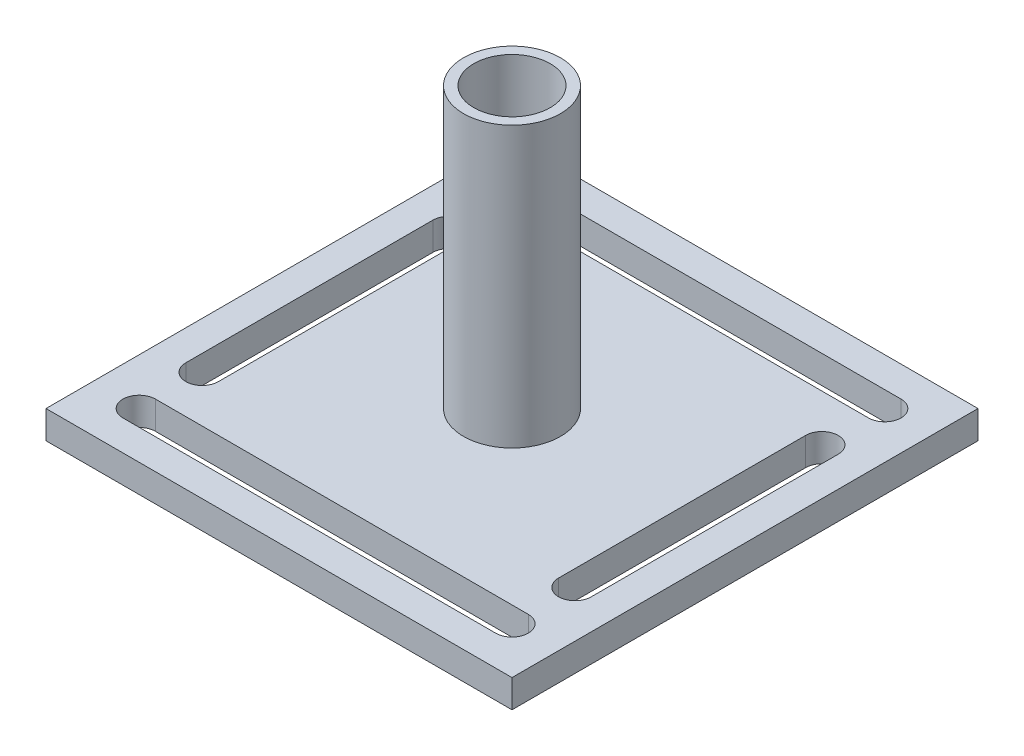
SolidWorks part; units mm, degrees
ref_plane "前视基准面" through (0, 0, 0) normal (0, 0, 1) x (1, 0, 0)
ref_plane "上视基准面" through (0, 0, 0) normal (0, 1, 0) x (1, 0, 0)
ref_plane "右视基准面" through (0, 0, 0) normal (1, 0, 0) x (0, 0, -1)
other "Configuration Table"
sketch "草图1" plane through (0, 0, 0) normal (0, 1, 0) x (1, 0, 0)
  line L1 (0, 0) -> (50, 0)
  line L2 (0, 0) -> (0, 50)
  line L3 (0, 50) -> (50, 50)
  line L4 (50, 0) -> (50, 50)
  dimension "D1" = 50
  dimension "D2" = 50
extrude "凸台-拉伸1" add sketch "草图1" along normal blind 3
sketch "草图2" plane through (0, 3, 0) normal (0, 1, 0) x (1, 0, 0)
  line L0 (0, 25) -> (50, 25) construction
  line L1 (0, 50) -> (0, 0) construction
  line L2 (50, 0) -> (50, 50) construction
  circle A0 centre (25, 25) radius 5.2
extrude "凸台-拉伸3" add sketch "草图2" along normal blind 30
sketch "草图4" plane through (0, 33, 0) normal (0, 1, 0) x (1, 0, 0)
  line L0 (19.8, 25) -> (30.2, 25) construction
  circle A0 centre (25, 25) radius 5.2 construction
  circle A1 centre (25, 25) radius 5.2 construction
  circle A2 centre (25, 25) radius 4.1
extrude "切除-拉伸1" cut sketch "草图4" against normal blind 30
sketch "草图6" plane through (0, 0, 0) normal (0, -1, 0) x (1, 0, 0)
  line L0 (50, -5) -> (45, -5) construction
  line L3 (0, -5) -> (5, -5) construction
  line L4 (5, 0) -> (5, -5) construction
  line L5 (50, 0) -> (50, -50) construction
  line L6 (5, -5) -> (45, -5) construction
  line L7 (5, -3.25) -> (45, -3.25)
  line L8 (5, -6.75) -> (45, -6.75)
  line L9 (5, -6.75) -> (5, -11.75)
  line L10 (0, -25) -> (50, -25) construction
  line L11 (0, -50) -> (0, 0) construction
  line L12 (5, -45) -> (45, -45) construction
  line L13 (5, -46.75) -> (45, -46.75)
  line L14 (5, -43.25) -> (45, -43.25)
  line L15 (5, -43.25) -> (5, -38.25)
  line L16 (5, -11.75) -> (5, -38.25) construction
  line L17 (6.75, -11.75) -> (6.75, -38.25)
  line L18 (3.25, -11.75) -> (3.25, -38.25)
  line L19 (25, 0) -> (25, -50) construction
  line L20 (0, 0) -> (50, 0) construction
  line L21 (50, -50) -> (0, -50) construction
  line L22 (45, -11.75) -> (45, -38.25) construction
  line L23 (43.25, -11.75) -> (43.25, -38.25)
  line L24 (46.75, -11.75) -> (46.75, -38.25)
  arc A0 (5, -3.25) -> (5, -6.75) centre (5, -5) ccw
  arc A1 (45, -6.75) -> (45, -3.25) centre (45, -5) ccw
  arc A2 (5, -46.75) -> (5, -43.25) centre (5, -45) cw
  arc A3 (45, -43.25) -> (45, -46.75) centre (45, -45) cw
  arc A4 (6.75, -11.75) -> (3.25, -11.75) centre (5, -11.75) ccw
  arc A5 (3.25, -38.25) -> (6.75, -38.25) centre (5, -38.25) ccw
  arc A6 (43.25, -11.75) -> (46.75, -11.75) centre (45, -11.75) cw
  arc A7 (46.75, -38.25) -> (43.25, -38.25) centre (45, -38.25) cw
  point P0 (25, -5)
  point P21 (25, -45)
  point P28 (5, -25)
  point P41 (45, -25)
  dimension "D4" = 5
  dimension "D1" = 5
  dimension "D2" = 5
  dimension "D3" = 5
  dimension "D5" = 5
extrude "切除-拉伸2" cut sketch "草图6" against normal blind 30
